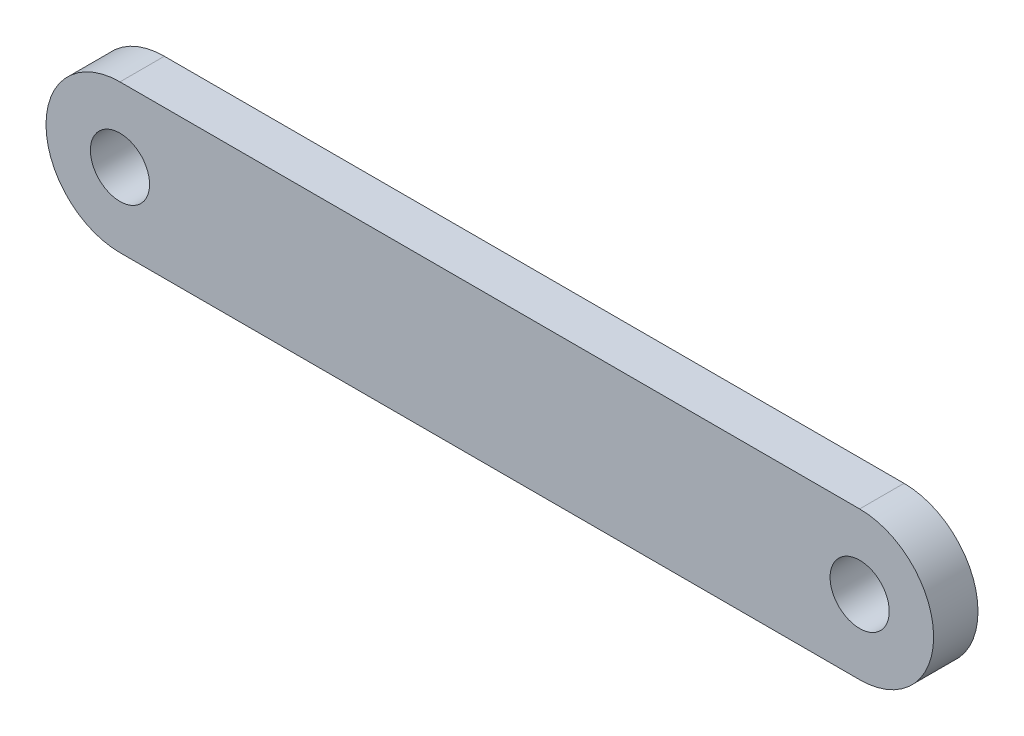
SolidWorks part; units mm, degrees
ref_plane "Front Plane" through (0, 0, 0) normal (0, 0, 1) x (1, 0, 0)
ref_plane "Top Plane" through (0, 0, 0) normal (0, 1, 0) x (1, 0, 0)
ref_plane "Right Plane" through (0, 0, 0) normal (1, 0, 0) x (0, 0, -1)
sketch "Sketch1" plane through (0, 34.7031, 0) normal (0, 0, 1) x (1, 0, 0)
  line L1 (44.5462, 243.4034) -> (94.5462, 243.4034)
  line L3 (44.5462, 233.4034) -> (94.5462, 233.4034)
  arc A0 (44.5462, 243.4034) -> (44.5462, 233.4034) centre (44.5462, 238.4034) ccw
  arc A1 (94.5462, 243.4034) -> (94.5462, 233.4034) centre (94.5462, 238.4034) cw
  circle A2 centre (44.5462, 238.4034) radius 2
  circle A3 centre (94.5462, 238.4034) radius 2
  point P9 (94.5938, 225.7295)
  point P10 (44.6391, 215.7729)
  point P11 (44.5895, 225.7421)
  dimension "D3" = 4
  dimension "D4" = 4
  dimension "D1" = 50
  dimension "D2" = 10
extrude "Boss-Extrude1" add sketch "Sketch1" along normal blind 3
